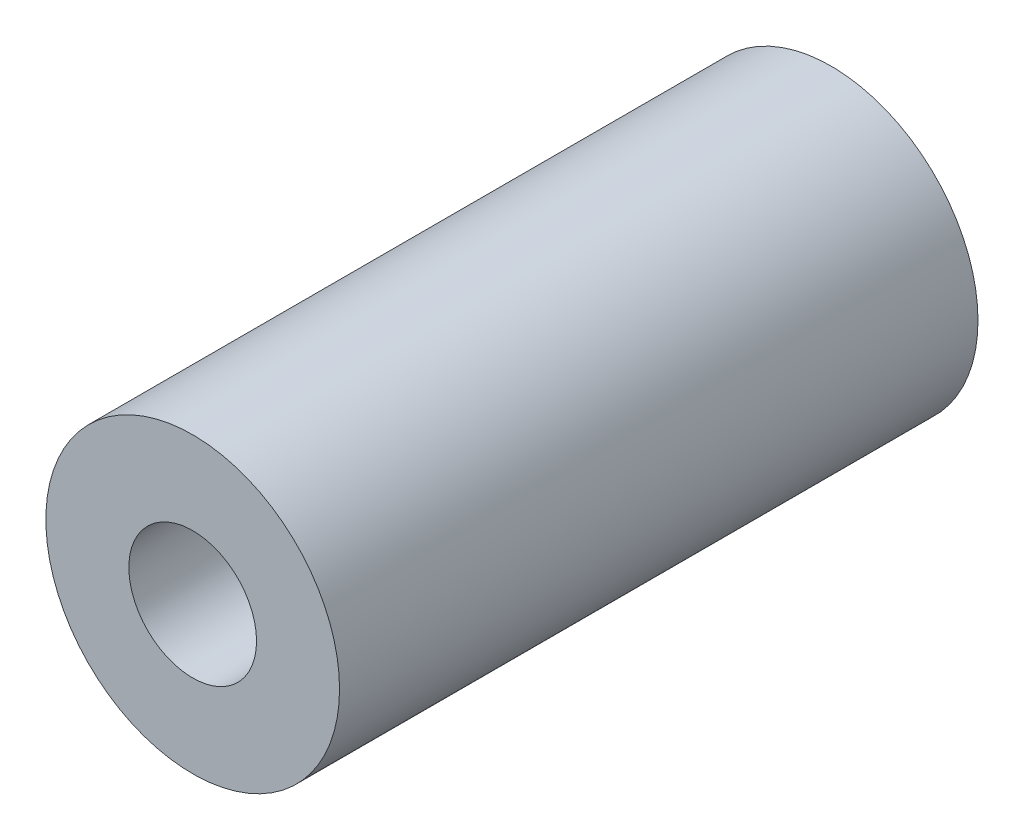
SolidWorks part; units mm, degrees
ref_plane "Front Plane" through (0, 0, 0) normal (0, 0, 1) x (1, 0, 0)
ref_plane "Top Plane" through (0, 0, 0) normal (0, 1, 0) x (1, 0, 0)
ref_plane "Right Plane" through (0, 0, 0) normal (1, 0, 0) x (0, 0, -1)
sketch "Sketch1" plane through (0, 0, 0) normal (0, 0, 1) x (1, 0, 0)
  circle A0 centre (0, 0) radius 2.3
  circle A1 centre (0, 0) radius 1
  dimension "D1" = 4.6
  dimension "D2" = 2
extrude "Boss-Extrude1" add sketch "Sketch1" along normal blind 10
